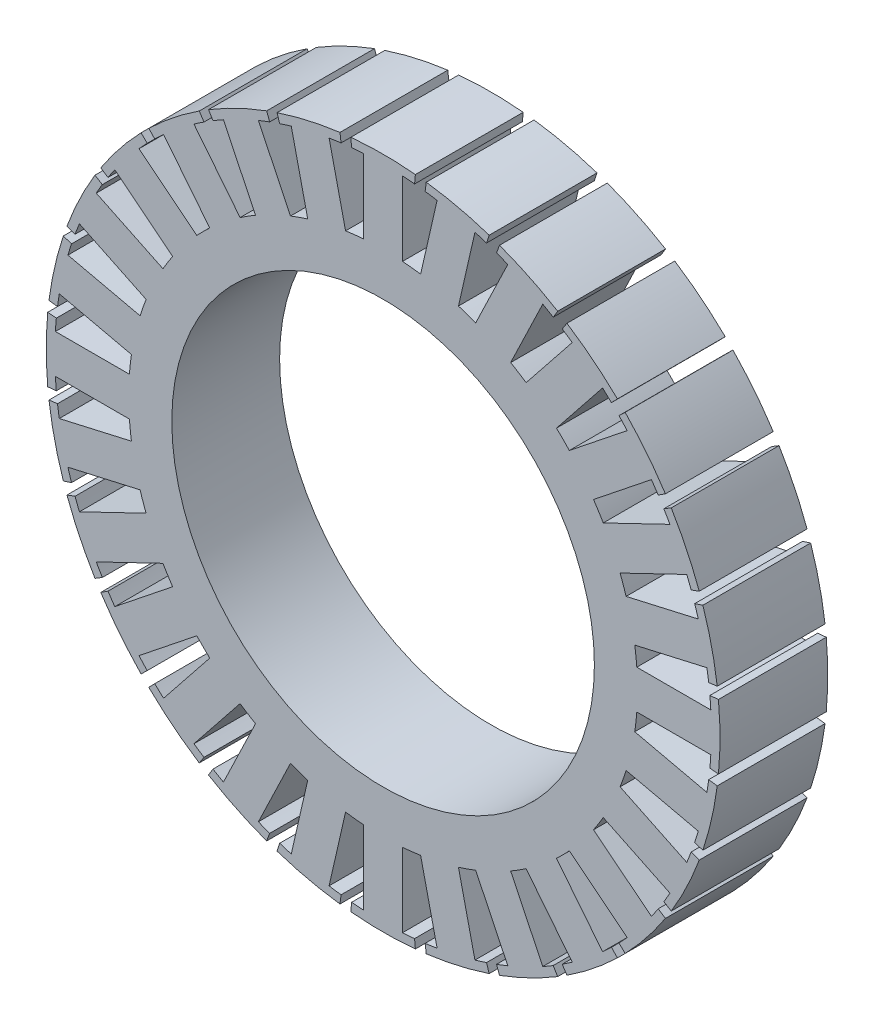
SolidWorks part; units mm, degrees
material "Copper"
ref_plane "Front Plane" through (0, 0, 0) normal (0, 0, 1) x (1, 0, 0)
ref_plane "Top Plane" through (0, 0, 0) normal (0, 1, 0) x (1, 0, 0)
ref_plane "Right Plane" through (0, 0, 0) normal (1, 0, 0) x (0, 0, -1)
sketch "Sketch2" plane through (0, 0, 0) normal (0, 0, 1) x (1, 0, 0)
  line L0 (0, 0) -> (0, 30.55) construction
  line L1 (-1.8, 30.3968) -> (-1.8, 23.5313)
  line L2 (-2.9952, 31.1061) -> (-2.9185, 30.3098)
  line L3 (2.9952, 31.1061) -> (2.9185, 30.3098)
  line L4 (1.8, 30.3968) -> (1.8, 23.5313)
  line L5 (5.009, 30.0352) -> (3.4813, 23.3418)
  line L6 (4.0017, 30.9927) -> (3.8992, 30.1993)
  line L7 (8.5188, 29.2341) -> (6.9911, 22.5407)
  line L8 (9.8418, 29.6597) -> (9.5899, 28.9005)
  line L9 (11.5669, 28.1675) -> (8.5881, 21.9819)
  line L10 (10.7979, 29.3252) -> (10.5215, 28.5745)
  line L11 (14.8104, 26.6055) -> (11.8316, 20.4199)
  line L12 (16.195, 26.7261) -> (15.7804, 26.0419)
  line L13 (17.5448, 24.8874) -> (13.2642, 19.5198)
  line L14 (17.0526, 26.1872) -> (16.6161, 25.5168)
  line L15 (20.3594, 22.6429) -> (16.0788, 17.2752)
  line L16 (21.7361, 22.4523) -> (21.1796, 21.8775)
  line L17 (22.6429, 20.3594) -> (17.2752, 16.0788)
  line L18 (22.4523, 21.7361) -> (21.8775, 21.1796)
  line L19 (24.8874, 17.5448) -> (19.5198, 13.2642)
  line L20 (26.1872, 17.0526) -> (25.5168, 16.6161)
  line L21 (26.6055, 14.8104) -> (20.4199, 11.8316)
  line L22 (26.7261, 16.195) -> (26.0419, 15.7804)
  line L23 (28.1675, 11.5669) -> (21.9819, 8.5881)
  line L24 (29.3252, 10.7979) -> (28.5745, 10.5215)
  line L25 (29.2341, 8.5188) -> (22.5407, 6.9911)
  line L26 (29.6597, 9.8418) -> (28.9005, 9.5899)
  line L27 (30.0352, 5.009) -> (23.3418, 3.4813)
  line L28 (30.9927, 4.0017) -> (30.1993, 3.8992)
  line L29 (30.3968, 1.8) -> (23.5313, 1.8)
  line L30 (31.1061, 2.9952) -> (30.3098, 2.9185)
  line L31 (30.3968, -1.8) -> (23.5313, -1.8)
  line L32 (31.1061, -2.9952) -> (30.3098, -2.9185)
  line L33 (30.0352, -5.009) -> (23.3418, -3.4813)
  line L34 (30.9927, -4.0017) -> (30.1993, -3.8992)
  line L35 (29.2341, -8.5188) -> (22.5407, -6.9911)
  line L36 (29.6597, -9.8418) -> (28.9005, -9.5899)
  line L37 (28.1675, -11.5669) -> (21.9819, -8.5881)
  line L38 (29.3252, -10.7979) -> (28.5745, -10.5215)
  line L39 (26.6055, -14.8104) -> (20.4199, -11.8316)
  line L40 (26.7261, -16.195) -> (26.0419, -15.7804)
  line L41 (24.8874, -17.5448) -> (19.5198, -13.2642)
  line L42 (26.1872, -17.0526) -> (25.5168, -16.6161)
  line L43 (22.6429, -20.3594) -> (17.2752, -16.0788)
  line L44 (22.4523, -21.7361) -> (21.8775, -21.1796)
  line L45 (20.3594, -22.6429) -> (16.0788, -17.2752)
  line L46 (21.7361, -22.4523) -> (21.1796, -21.8775)
  line L47 (17.5448, -24.8874) -> (13.2642, -19.5198)
  line L48 (17.0526, -26.1872) -> (16.6161, -25.5168)
  line L49 (14.8104, -26.6055) -> (11.8316, -20.4199)
  line L50 (16.195, -26.7261) -> (15.7804, -26.0419)
  line L51 (11.5669, -28.1675) -> (8.5881, -21.9819)
  line L52 (10.7979, -29.3252) -> (10.5215, -28.5745)
  line L53 (8.5188, -29.2341) -> (6.9911, -22.5407)
  line L54 (9.8418, -29.6597) -> (9.5899, -28.9005)
  line L55 (5.009, -30.0352) -> (3.4813, -23.3418)
  line L56 (4.0017, -30.9927) -> (3.8992, -30.1993)
  line L57 (1.8, -30.3968) -> (1.8, -23.5313)
  line L58 (2.9952, -31.1061) -> (2.9185, -30.3098)
  line L59 (-1.8, -30.3968) -> (-1.8, -23.5313)
  line L60 (-2.9952, -31.1061) -> (-2.9185, -30.3098)
  line L61 (-5.009, -30.0352) -> (-3.4813, -23.3418)
  line L62 (-4.0017, -30.9927) -> (-3.8992, -30.1993)
  line L63 (-8.5188, -29.2341) -> (-6.9911, -22.5407)
  line L64 (-9.8418, -29.6597) -> (-9.5899, -28.9005)
  line L65 (-11.5669, -28.1675) -> (-8.5881, -21.9819)
  line L66 (-10.7979, -29.3252) -> (-10.5215, -28.5745)
  line L67 (-14.8104, -26.6055) -> (-11.8316, -20.4199)
  line L68 (-16.195, -26.7261) -> (-15.7804, -26.0419)
  line L69 (-17.5448, -24.8874) -> (-13.2642, -19.5198)
  line L70 (-17.0526, -26.1872) -> (-16.6161, -25.5168)
  line L71 (-20.3594, -22.6429) -> (-16.0788, -17.2752)
  line L72 (-21.7361, -22.4523) -> (-21.1796, -21.8775)
  line L73 (-22.6429, -20.3594) -> (-17.2752, -16.0788)
  line L74 (-22.4523, -21.7361) -> (-21.8775, -21.1796)
  line L75 (-24.8874, -17.5448) -> (-19.5198, -13.2642)
  line L76 (-26.1872, -17.0526) -> (-25.5168, -16.6161)
  line L77 (-26.6055, -14.8104) -> (-20.4199, -11.8316)
  line L78 (-26.7261, -16.195) -> (-26.0419, -15.7804)
  line L79 (-28.1675, -11.5669) -> (-21.9819, -8.5881)
  line L80 (-29.3252, -10.7979) -> (-28.5745, -10.5215)
  line L81 (-29.2341, -8.5188) -> (-22.5407, -6.9911)
  line L82 (-29.6597, -9.8418) -> (-28.9005, -9.5899)
  line L83 (-30.0352, -5.009) -> (-23.3418, -3.4813)
  line L84 (-30.9927, -4.0017) -> (-30.1993, -3.8992)
  line L85 (-30.3968, -1.8) -> (-23.5313, -1.8)
  line L86 (-31.1061, -2.9952) -> (-30.3098, -2.9185)
  line L87 (-30.3968, 1.8) -> (-23.5313, 1.8)
  line L88 (-31.1061, 2.9952) -> (-30.3098, 2.9185)
  line L89 (-30.0352, 5.009) -> (-23.3418, 3.4813)
  line L90 (-30.9927, 4.0017) -> (-30.1993, 3.8992)
  line L91 (-29.2341, 8.5188) -> (-22.5407, 6.9911)
  line L92 (-29.6597, 9.8418) -> (-28.9005, 9.5899)
  line L93 (-28.1675, 11.5669) -> (-21.9819, 8.5881)
  line L94 (-29.3252, 10.7979) -> (-28.5745, 10.5215)
  line L95 (-26.6055, 14.8104) -> (-20.4199, 11.8316)
  line L96 (-26.7261, 16.195) -> (-26.0419, 15.7804)
  line L97 (-24.8874, 17.5448) -> (-19.5198, 13.2642)
  line L98 (-26.1872, 17.0526) -> (-25.5168, 16.6161)
  line L99 (-22.6429, 20.3594) -> (-17.2752, 16.0788)
  line L100 (-22.4523, 21.7361) -> (-21.8775, 21.1796)
  line L101 (-20.3594, 22.6429) -> (-16.0788, 17.2752)
  line L102 (-21.7361, 22.4523) -> (-21.1796, 21.8775)
  line L103 (-17.5448, 24.8874) -> (-13.2642, 19.5198)
  line L104 (-17.0526, 26.1872) -> (-16.6161, 25.5168)
  line L105 (-14.8104, 26.6055) -> (-11.8316, 20.4199)
  line L106 (-16.195, 26.7261) -> (-15.7804, 26.0419)
  line L107 (-11.5669, 28.1675) -> (-8.5881, 21.9819)
  line L108 (-10.7979, 29.3252) -> (-10.5215, 28.5745)
  line L109 (-8.5188, 29.2341) -> (-6.9911, 22.5407)
  line L110 (-9.8418, 29.6597) -> (-9.5899, 28.9005)
  line L111 (-5.009, 30.0352) -> (-3.4813, 23.3418)
  line L112 (-4.0017, 30.9927) -> (-3.8992, 30.1993)
  arc A0 (-19.5198, 13.2642) -> (-20.4199, 11.8316) centre (0, 0) ccw
  circle A1 centre (0, 0) radius 32.05 construction
  arc A2 (2.9952, 31.1061) -> (-2.9952, 31.1061) centre (0, 0) ccw
  arc A3 (-1.8, 30.3968) -> (-2.9185, 30.3098) centre (0, 0) ccw
  arc A4 (1.8, 30.3968) -> (2.9185, 30.3098) centre (0, 0) cw
  circle A5 centre (0, 0) radius 31.25 construction
  circle A6 centre (0, 0) radius 30.45 construction
  arc A7 (5.009, 30.0352) -> (3.8992, 30.1993) centre (0, 0) ccw
  arc A8 (9.8418, 29.6597) -> (4.0017, 30.9927) centre (0, 0) ccw
  arc A9 (8.5188, 29.2341) -> (9.5899, 28.9005) centre (0, 0) cw
  arc A10 (11.5669, 28.1675) -> (10.5215, 28.5745) centre (0, 0) ccw
  arc A11 (16.195, 26.7261) -> (10.7979, 29.3252) centre (0, 0) ccw
  arc A12 (14.8104, 26.6055) -> (15.7804, 26.0419) centre (0, 0) cw
  arc A13 (17.5448, 24.8874) -> (16.6161, 25.5168) centre (0, 0) ccw
  arc A14 (21.7361, 22.4523) -> (17.0526, 26.1872) centre (0, 0) ccw
  arc A15 (20.3594, 22.6429) -> (21.1796, 21.8775) centre (0, 0) cw
  arc A16 (22.6429, 20.3594) -> (21.8775, 21.1796) centre (0, 0) ccw
  arc A17 (26.1872, 17.0526) -> (22.4523, 21.7361) centre (0, 0) ccw
  arc A18 (24.8874, 17.5448) -> (25.5168, 16.6161) centre (0, 0) cw
  arc A19 (26.6055, 14.8104) -> (26.0419, 15.7804) centre (0, 0) ccw
  arc A20 (29.3252, 10.7979) -> (26.7261, 16.195) centre (0, 0) ccw
  arc A21 (28.1675, 11.5669) -> (28.5745, 10.5215) centre (0, 0) cw
  arc A22 (29.2341, 8.5188) -> (28.9005, 9.5899) centre (0, 0) ccw
  arc A23 (30.9927, 4.0017) -> (29.6597, 9.8418) centre (0, 0) ccw
  arc A24 (30.0352, 5.009) -> (30.1993, 3.8992) centre (0, 0) cw
  arc A25 (30.3968, 1.8) -> (30.3098, 2.9185) centre (0, 0) ccw
  arc A26 (31.1061, -2.9952) -> (31.1061, 2.9952) centre (0, 0) ccw
  arc A27 (30.3968, -1.8) -> (30.3098, -2.9185) centre (0, 0) cw
  arc A28 (30.0352, -5.009) -> (30.1993, -3.8992) centre (0, 0) ccw
  arc A29 (29.6597, -9.8418) -> (30.9927, -4.0017) centre (0, 0) ccw
  arc A30 (29.2341, -8.5188) -> (28.9005, -9.5899) centre (0, 0) cw
  arc A31 (28.1675, -11.5669) -> (28.5745, -10.5215) centre (0, 0) ccw
  arc A32 (26.7261, -16.195) -> (29.3252, -10.7979) centre (0, 0) ccw
  arc A33 (26.6055, -14.8104) -> (26.0419, -15.7804) centre (0, 0) cw
  arc A34 (24.8874, -17.5448) -> (25.5168, -16.6161) centre (0, 0) ccw
  arc A35 (22.4523, -21.7361) -> (26.1872, -17.0526) centre (0, 0) ccw
  arc A36 (22.6429, -20.3594) -> (21.8775, -21.1796) centre (0, 0) cw
  arc A37 (20.3594, -22.6429) -> (21.1796, -21.8775) centre (0, 0) ccw
  arc A38 (17.0526, -26.1872) -> (21.7361, -22.4523) centre (0, 0) ccw
  arc A39 (17.5448, -24.8874) -> (16.6161, -25.5168) centre (0, 0) cw
  arc A40 (14.8104, -26.6055) -> (15.7804, -26.0419) centre (0, 0) ccw
  arc A41 (10.7979, -29.3252) -> (16.195, -26.7261) centre (0, 0) ccw
  arc A42 (11.5669, -28.1675) -> (10.5215, -28.5745) centre (0, 0) cw
  arc A43 (8.5188, -29.2341) -> (9.5899, -28.9005) centre (0, 0) ccw
  arc A44 (4.0017, -30.9927) -> (9.8418, -29.6597) centre (0, 0) ccw
  arc A45 (5.009, -30.0352) -> (3.8992, -30.1993) centre (0, 0) cw
  arc A46 (1.8, -30.3968) -> (2.9185, -30.3098) centre (0, 0) ccw
  arc A47 (-2.9952, -31.1061) -> (2.9952, -31.1061) centre (0, 0) ccw
  arc A48 (-1.8, -30.3968) -> (-2.9185, -30.3098) centre (0, 0) cw
  arc A49 (-5.009, -30.0352) -> (-3.8992, -30.1993) centre (0, 0) ccw
  arc A50 (-9.8418, -29.6597) -> (-4.0017, -30.9927) centre (0, 0) ccw
  arc A51 (-8.5188, -29.2341) -> (-9.5899, -28.9005) centre (0, 0) cw
  arc A52 (-11.5669, -28.1675) -> (-10.5215, -28.5745) centre (0, 0) ccw
  arc A53 (-16.195, -26.7261) -> (-10.7979, -29.3252) centre (0, 0) ccw
  arc A54 (-14.8104, -26.6055) -> (-15.7804, -26.0419) centre (0, 0) cw
  arc A55 (-17.5448, -24.8874) -> (-16.6161, -25.5168) centre (0, 0) ccw
  arc A56 (-21.7361, -22.4523) -> (-17.0526, -26.1872) centre (0, 0) ccw
  arc A57 (-20.3594, -22.6429) -> (-21.1796, -21.8775) centre (0, 0) cw
  arc A58 (-22.6429, -20.3594) -> (-21.8775, -21.1796) centre (0, 0) ccw
  arc A59 (-26.1872, -17.0526) -> (-22.4523, -21.7361) centre (0, 0) ccw
  arc A60 (-24.8874, -17.5448) -> (-25.5168, -16.6161) centre (0, 0) cw
  arc A61 (-26.6055, -14.8104) -> (-26.0419, -15.7804) centre (0, 0) ccw
  arc A62 (-29.3252, -10.7979) -> (-26.7261, -16.195) centre (0, 0) ccw
  arc A63 (-28.1675, -11.5669) -> (-28.5745, -10.5215) centre (0, 0) cw
  arc A64 (-29.2341, -8.5188) -> (-28.9005, -9.5899) centre (0, 0) ccw
  arc A65 (-30.9927, -4.0017) -> (-29.6597, -9.8418) centre (0, 0) ccw
  arc A66 (-30.0352, -5.009) -> (-30.1993, -3.8992) centre (0, 0) cw
  arc A67 (-30.3968, -1.8) -> (-30.3098, -2.9185) centre (0, 0) ccw
  arc A68 (-31.1061, 2.9952) -> (-31.1061, -2.9952) centre (0, 0) ccw
  arc A69 (-30.3968, 1.8) -> (-30.3098, 2.9185) centre (0, 0) cw
  arc A70 (-30.0352, 5.009) -> (-30.1993, 3.8992) centre (0, 0) ccw
  arc A71 (-29.6597, 9.8418) -> (-30.9927, 4.0017) centre (0, 0) ccw
  arc A72 (-29.2341, 8.5188) -> (-28.9005, 9.5899) centre (0, 0) cw
  arc A73 (-28.1675, 11.5669) -> (-28.5745, 10.5215) centre (0, 0) ccw
  arc A74 (-26.7261, 16.195) -> (-29.3252, 10.7979) centre (0, 0) ccw
  arc A75 (-26.6055, 14.8104) -> (-26.0419, 15.7804) centre (0, 0) cw
  arc A76 (-24.8874, 17.5448) -> (-25.5168, 16.6161) centre (0, 0) ccw
  arc A77 (-22.4523, 21.7361) -> (-26.1872, 17.0526) centre (0, 0) ccw
  arc A78 (-22.6429, 20.3594) -> (-21.8775, 21.1796) centre (0, 0) cw
  arc A79 (-20.3594, 22.6429) -> (-21.1796, 21.8775) centre (0, 0) ccw
  arc A80 (-17.0526, 26.1872) -> (-21.7361, 22.4523) centre (0, 0) ccw
  arc A81 (-17.5448, 24.8874) -> (-16.6161, 25.5168) centre (0, 0) cw
  arc A82 (-14.8104, 26.6055) -> (-15.7804, 26.0419) centre (0, 0) ccw
  arc A83 (-10.7979, 29.3252) -> (-16.195, 26.7261) centre (0, 0) ccw
  arc A84 (-11.5669, 28.1675) -> (-10.5215, 28.5745) centre (0, 0) cw
  arc A85 (-8.5188, 29.2341) -> (-9.5899, 28.9005) centre (0, 0) ccw
  arc A86 (-4.0017, 30.9927) -> (-9.8418, 29.6597) centre (0, 0) ccw
  arc A87 (-5.009, 30.0352) -> (-3.8992, 30.1993) centre (0, 0) cw
  arc A88 (-21.9819, 8.5881) -> (-22.5407, 6.9911) centre (0, 0) ccw
  arc A89 (-23.3418, 3.4813) -> (-23.5313, 1.8) centre (0, 0) ccw
  arc A90 (-23.5313, -1.8) -> (-23.3418, -3.4813) centre (0, 0) ccw
  arc A91 (-22.5407, -6.9911) -> (-21.9819, -8.5881) centre (0, 0) ccw
  arc A92 (-20.4199, -11.8316) -> (-19.5198, -13.2642) centre (0, 0) ccw
  arc A93 (-17.2752, -16.0788) -> (-16.0788, -17.2752) centre (0, 0) ccw
  arc A94 (-13.2642, -19.5198) -> (-11.8316, -20.4199) centre (0, 0) ccw
  arc A95 (-8.5881, -21.9819) -> (-6.9911, -22.5407) centre (0, 0) ccw
  arc A96 (-3.4813, -23.3418) -> (-1.8, -23.5313) centre (0, 0) ccw
  arc A97 (1.8, -23.5313) -> (3.4813, -23.3418) centre (0, 0) ccw
  arc A98 (6.9911, -22.5407) -> (8.5881, -21.9819) centre (0, 0) ccw
  arc A99 (11.8316, -20.4199) -> (13.2642, -19.5198) centre (0, 0) ccw
  arc A100 (16.0788, -17.2752) -> (17.2752, -16.0788) centre (0, 0) ccw
  arc A101 (19.5198, -13.2642) -> (20.4199, -11.8316) centre (0, 0) ccw
  arc A102 (21.9819, -8.5881) -> (22.5407, -6.9911) centre (0, 0) ccw
  arc A103 (23.3418, -3.4813) -> (23.5313, -1.8) centre (0, 0) ccw
  arc A104 (23.5313, 1.8) -> (23.3418, 3.4813) centre (0, 0) ccw
  arc A105 (22.5407, 6.9911) -> (21.9819, 8.5881) centre (0, 0) ccw
  arc A106 (17.2752, 16.0788) -> (16.0788, 17.2752) centre (0, 0) ccw
  arc A107 (20.4199, 11.8316) -> (19.5198, 13.2642) centre (0, 0) ccw
  arc A108 (13.2642, 19.5198) -> (11.8316, 20.4199) centre (0, 0) ccw
  arc A109 (8.5881, 21.9819) -> (6.9911, 22.5407) centre (0, 0) ccw
  arc A110 (3.4813, 23.3418) -> (1.8, 23.5313) centre (0, 0) ccw
  arc A111 (-1.8, 23.5313) -> (-3.4813, 23.3418) centre (0, 0) ccw
  arc A112 (-6.9911, 22.5407) -> (-8.5881, 21.9819) centre (0, 0) ccw
  arc A113 (-11.8316, 20.4199) -> (-13.2642, 19.5198) centre (0, 0) ccw
  arc A114 (-16.0788, 17.2752) -> (-17.2752, 16.0788) centre (0, 0) ccw
  circle A115 centre (0, 0) radius 19.6
  point P5 (30.05, 0)
  point P15 (29.2151, 8.932)
  dimension "D1" = 64.1
  dimension "D2" = 4
  dimension "D8" = 39.2
  dimension "D5" = 5.5
  dimension "D6" = 1.8
  dimension "D3" = 0.8
  dimension "D4" = 0.8
  dimension "D7" = 28
extrude "Boss-Extrude1" add sketch "Sketch2" against normal blind 10 contours A0
